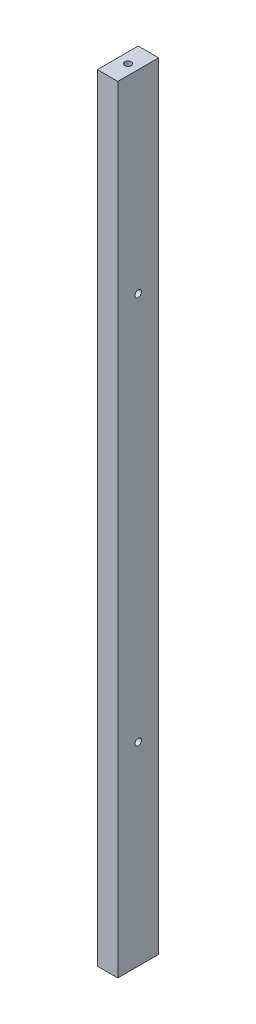
SolidWorks part; units mm, degrees
ref_plane "Спереди" through (0, 0, 0) normal (0, 0, 1) x (1, 0, 0)
ref_plane "Сверху" through (0, 0, 0) normal (0, 1, 0) x (1, 0, 0)
ref_plane "Справа" through (0, 0, 0) normal (1, 0, 0) x (0, 0, -1)
other "Configuration Table"
sketch "Эскиз1" plane through (0, 0, 0) normal (0, 1, 0) x (1, 0, 0)
  line L1 (12.5, 25) -> (-12.5, 25)
  line L2 (12.5, 25) -> (12.5, -25)
  line L3 (12.5, -25) -> (-12.5, -25)
  line L4 (-12.5, 25) -> (-12.5, -25)
  line L5 (12.5, 25) -> (-12.5, -25) construction
  line L6 (12.5, -25) -> (-12.5, 25) construction
  point P0 (0, 0)
extrude "Бобышка-Вытянуть1" add sketch "Эскиз1" along normal blind 950
sketch "Эскиз2" plane through (12.5, 0, 0) normal (1, 0, 0) x (0, 0, -1)
  circle A0 centre (0, 712.5) radius 4
  circle A1 centre (0, 237.5) radius 4
extrude "Вырез-Вытянуть1" cut sketch "Эскиз2" against normal blind 950
sketch "Эскиз3" plane through (0, 950, 0) normal (0, 1, 0) x (1, 0, 0)
  circle A0 centre (0, 0) radius 4
extrude "Вырез-Вытянуть2" cut sketch "Эскиз3" against normal blind 10
sketch "Эскиз4" plane through (0, 0, 0) normal (0, -1, 0) x (1, 0, 0)
  circle A0 centre (0, 0) radius 4
extrude "Вырез-Вытянуть3" cut sketch "Эскиз4" against normal blind 10
